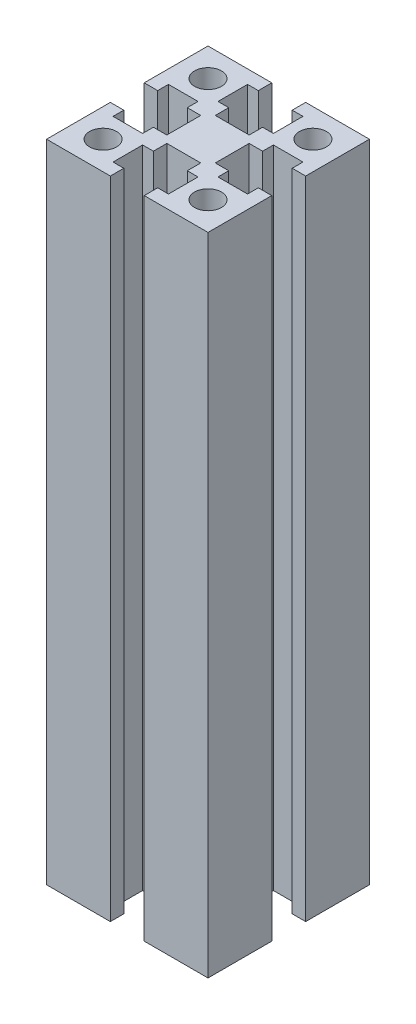
SolidWorks part; units mm, degrees
ref_plane "前视基准面" through (0, 0, 0) normal (0, 0, 1) x (1, 0, 0)
ref_plane "上视基准面" through (0, 0, 0) normal (0, 1, 0) x (1, 0, 0)
ref_plane "右视基准面" through (0, 0, 0) normal (1, 0, 0) x (0, 0, -1)
sketch "草图1" plane through (0, 0, 0) normal (0, 1, 0) x (1, 0, 0)
  line L0 (-15, -3.15) -> (-12.5, -3.15)
  line L1 (-15, 15) -> (-3.15, 15)
  line L2 (-15, 15) -> (-15, 3.15)
  line L3 (-15, -15) -> (-3.15, -15)
  line L4 (15, 15) -> (15, 3.15)
  line L5 (-15, 15) -> (15, -15) construction
  line L6 (-15, -15) -> (15, 15) construction
  line L7 (-12.5, -3.15) -> (-12.5, -5.15)
  line L8 (-12.5, -5.15) -> (-7, -5.15)
  line L9 (-7, -5.15) -> (-7, -3.15)
  line L10 (-7, -3.15) -> (-4.5, -3.15)
  line L11 (-4.5, -3.15) -> (-4.5, 3.15)
  line L12 (-4.5, 3.15) -> (-7, 3.15)
  line L13 (-7, 3.15) -> (-7, 5.15)
  line L14 (-7, 5.15) -> (-12.5, 5.15)
  line L15 (-12.5, 5.15) -> (-12.5, 3.15)
  line L16 (-12.5, 3.15) -> (-15, 3.15)
  line L17 (-15, 0) -> (-4.5, 0) construction
  line L18 (-15, -3.15) -> (-15, -15)
  line L19 (-15, 3.15) -> (-15, 0) construction
  line L20 (-15, 0) -> (-15, -3.15) construction
  line L21 (3.15, 12.5) -> (3.15, 15)
  line L22 (5.15, 12.5) -> (3.15, 12.5)
  line L23 (5.15, 7) -> (5.15, 12.5)
  line L24 (3.15, 7) -> (5.15, 7)
  line L25 (3.15, 4.5) -> (3.15, 7)
  line L26 (-3.15, 4.5) -> (3.15, 4.5)
  line L27 (-3.15, 7) -> (-3.15, 4.5)
  line L28 (-5.15, 7) -> (-3.15, 7)
  line L29 (-5.15, 12.5) -> (-5.15, 7)
  line L30 (-3.15, 12.5) -> (-5.15, 12.5)
  line L31 (-3.15, 15) -> (-3.15, 12.5)
  line L32 (12.5, -3.15) -> (15, -3.15)
  line L33 (12.5, -5.15) -> (12.5, -3.15)
  line L34 (7, -5.15) -> (12.5, -5.15)
  line L35 (7, -3.15) -> (7, -5.15)
  line L36 (4.5, -3.15) -> (7, -3.15)
  line L37 (4.5, 3.15) -> (4.5, -3.15)
  line L38 (7, 3.15) -> (4.5, 3.15)
  line L39 (7, 5.15) -> (7, 3.15)
  line L40 (12.5, 5.15) -> (7, 5.15)
  line L41 (12.5, 3.15) -> (12.5, 5.15)
  line L42 (15, 3.15) -> (12.5, 3.15)
  line L43 (-3.15, -12.5) -> (-3.15, -15)
  line L44 (-5.15, -12.5) -> (-3.15, -12.5)
  line L45 (-5.15, -7) -> (-5.15, -12.5)
  line L46 (-3.15, -7) -> (-5.15, -7)
  line L47 (-3.15, -4.5) -> (-3.15, -7)
  line L48 (3.15, -4.5) -> (-3.15, -4.5)
  line L49 (3.15, -7) -> (3.15, -4.5)
  line L50 (5.15, -7) -> (3.15, -7)
  line L51 (5.15, -12.5) -> (5.15, -7)
  line L52 (3.15, -12.5) -> (5.15, -12.5)
  line L53 (3.15, -15) -> (3.15, -12.5)
  line L54 (3.15, 15) -> (15, 15)
  line L55 (15, -3.15) -> (15, -15)
  line L56 (3.15, -15) -> (15, -15)
  line L57 (-5.15, -9.75) -> (-15, -9.75) construction
  line L58 (-9.75, -5.15) -> (-9.75, -15) construction
  circle A0 centre (-9.75, -9.75) radius 2.5
  circle A1 centre (-9.75, 9.75) radius 2.5
  circle A2 centre (9.75, 9.75) radius 2.5
  circle A3 centre (9.75, -9.75) radius 2.5
  point P0 (0, 0)
  point P59 (0, 0)
  point P72 (0, 0)
  dimension "D1" = 5
  dimension "D2" = 6.3
  dimension "D3" = 10.3
  dimension "D4" = 2.5
  dimension "D5" = 5.5
  dimension "D6" = 10.5
  dimension "D7" = 30
  dimension "D8" = 4
  dimension "D9" = 4
extrude "凸台-拉伸1" add sketch "草图1" along normal mid plane 360
sketch "草图2" plane through (0, 180, 0) normal (0, 1, 0) x (1, 0, 0)
  circle A0 centre (0, 0) radius 82.2505
extrude "切除-拉伸1" cut sketch "草图2" against normal blind 10
sketch "草图3" plane through (0, -180, 0) normal (0, -1, 0) x (1, 0, 0)
  circle A0 centre (0.2164, -1.772) radius 47.3598
extrude "切除-拉伸2" cut sketch "草图3" against normal blind 200
sketch "草图4" plane through (0, 20, 0) normal (0, -1, 0) x (1, 0, 0)
  circle A0 centre (-1.2874, -1.5436) radius 50.0559
extrude "切除-拉伸3" cut sketch "草图4" against normal blind 30
equation "\"零件重量\"= \"SW-质量\" / 1000"
